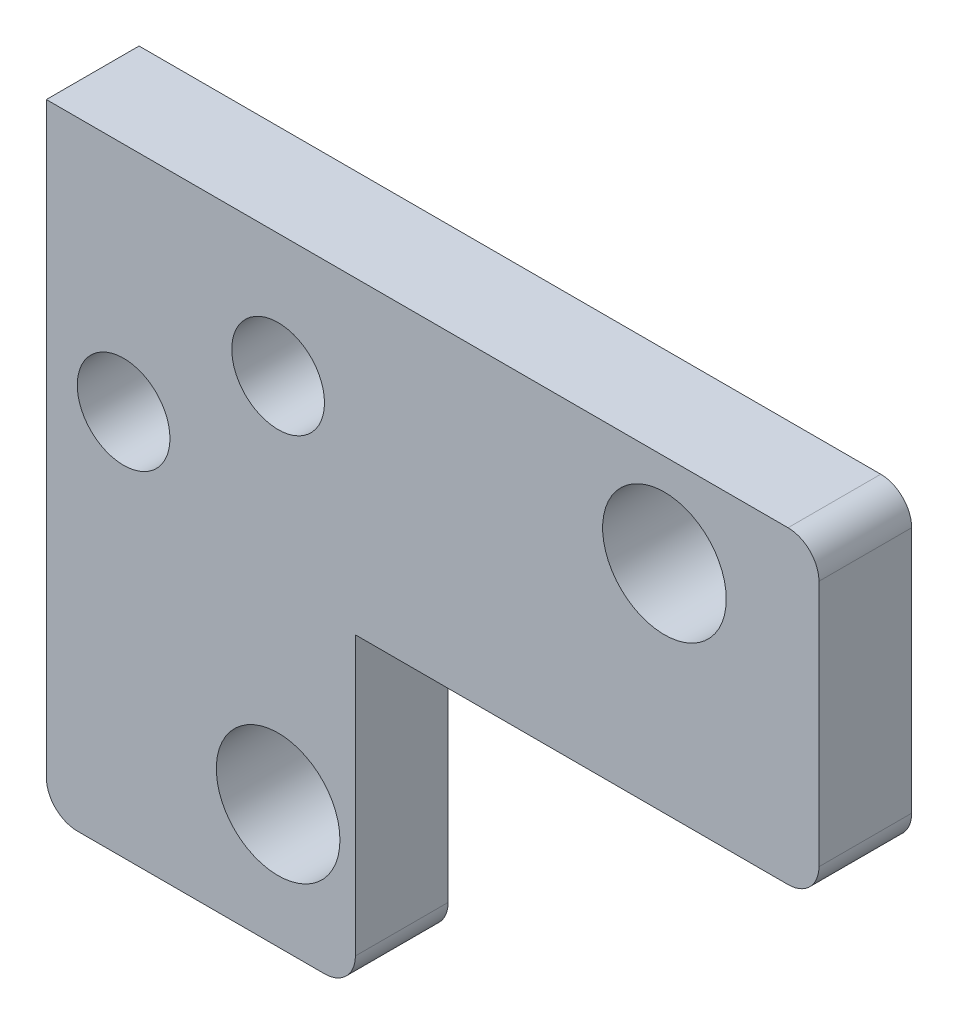
SolidWorks part; units mm, degrees
ref_plane "前视基准面" through (0, 0, 0) normal (0, 0, 1) x (1, 0, 0)
ref_plane "上视基准面" through (0, 0, 0) normal (0, 1, 0) x (1, 0, 0)
ref_plane "右视基准面" through (0, 0, 0) normal (1, 0, 0) x (0, 0, -1)
sketch "草图1" plane through (0, 0, 0) normal (0, 0, 1) x (1, 0, 0)
  line L1 (0, 0) -> (25, 0)
  line L2 (0, 0) -> (0, 10)
  line L3 (0, 10) -> (25, 10)
  line L4 (25, 0) -> (25, 10)
  line L5 (0, 0) -> (25, 10) construction
  line L6 (0, 10) -> (25, 0) construction
  point P4 (12.5, 5)
  dimension "D1" = 25
  dimension "D2" = 10
extrude "凸台-拉伸1" add sketch "草图1" along normal blind 3
sketch "草图2" plane through (0, 0, 3) normal (0, 0, 1) x (1, 0, 0)
  line L0 (0, 10) -> (0, 0) construction
  line L1 (0, 0) -> (25, 0) construction
  line L2 (25, 10) -> (0, 10) construction
  circle A0 centre (2.5, 2.5) radius 1.5
  circle A1 centre (7.5, 6) radius 1.5
  dimension "D1" = 3
  dimension "D2" = 3
  dimension "D4" = 2.5
  dimension "D3" = 2.5
  dimension "D5" = 4
  dimension "D6" = 7.5
extrude "切除-拉伸1" cut sketch "草图2" against normal blind 3
sketch "草图3" plane through (0, 0, 3) normal (0, 0, 1) x (1, 0, 0)
  line L0 (25, 10) -> (0, 10) construction
  line L1 (25, 0) -> (25, 10) construction
  circle A0 centre (20, 7) radius 2
  dimension "D1" = 4
  dimension "D2" = 3
  dimension "D3" = 5
extrude "切除-拉伸2" cut sketch "草图3" against normal blind 10
sketch "草图4" plane through (0, 0, 3) normal (0, 0, 1) x (1, 0, 0)
  line L1 (0, 0) -> (10, 0)
  line L2 (0, 0) -> (0, -10)
  line L3 (0, -10) -> (10, -10)
  line L4 (10, 0) -> (10, -10)
  line L5 (0, 0) -> (10, -10) construction
  line L6 (0, -10) -> (10, 0) construction
  point P4 (5, -5)
  dimension "D1" = 10
  dimension "D2" = 10
extrude "凸台-拉伸2" add sketch "草图4" against normal blind 3
sketch "草图5" plane through (0, 0, 3) normal (0, 0, 1) x (1, 0, 0)
  line L0 (10, -10) -> (10, 0) construction
  line L1 (0, -10) -> (10, -10) construction
  circle A0 centre (7.5, -6) radius 2
  dimension "D1" = 4
  dimension "D3" = 4
  dimension "D2" = 2.5
extrude "切除-拉伸3" cut sketch "草图5" against normal blind 3
fillet "圆角1" radius 1 4 edges at (0, -10, 1.5) (10, -10, 1.5) (25, 10, 1.5) (25, 0, 1.5)
